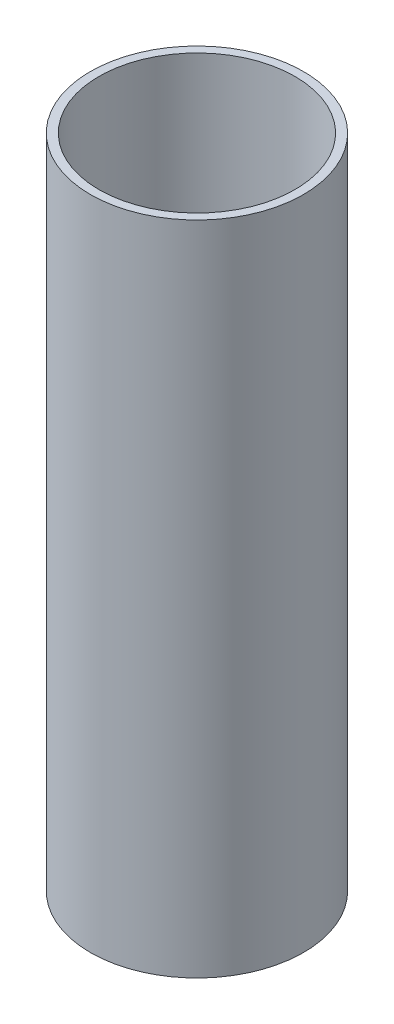
SolidWorks part; units mm, degrees
ref_plane "Front Plane" through (0, 0, 0) normal (0, 0, 1) x (1, 0, 0)
ref_plane "Top Plane" through (0, 0, 0) normal (0, 1, 0) x (1, 0, 0)
ref_plane "Right Plane" through (0, 0, 0) normal (1, 0, 0) x (0, 0, -1)
sketch "Sketch1" plane through (0, 0, 0) normal (0, 1, 0) x (1, 0, 0)
  circle A0 centre (0, 0) radius 11.5
  circle A1 centre (0, 0) radius 12.5
  dimension "D1" = 23
  dimension "D2" = 25
extrude "Boss-Extrude1" add sketch "Sketch1" along normal blind 77
